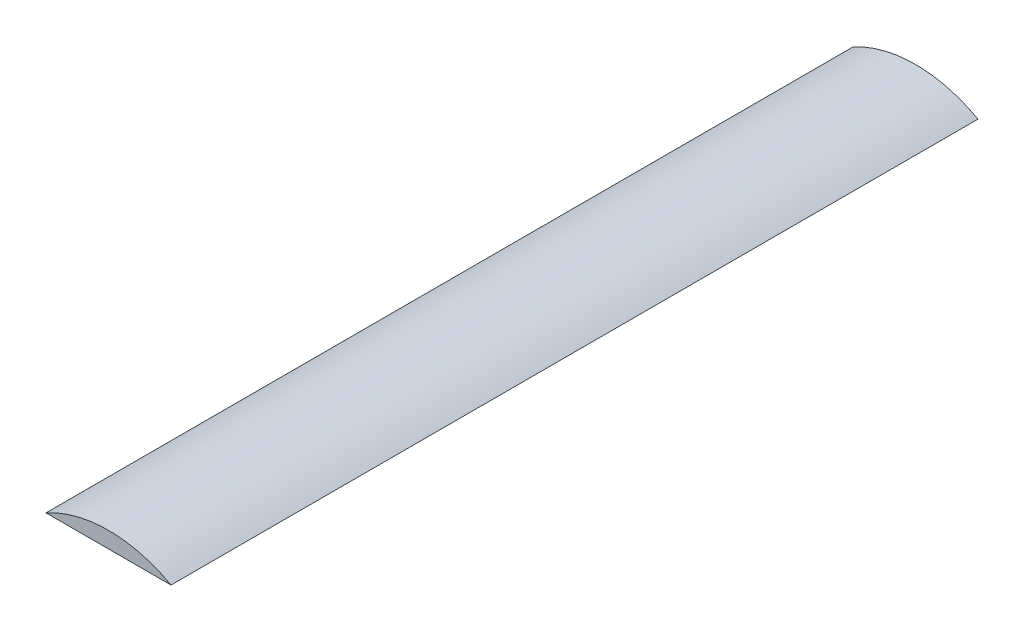
SolidWorks part; units mm, degrees
ref_plane "前视基准面" through (0, 0, 0) normal (0, 0, 1) x (1, 0, 0)
ref_plane "上视基准面" through (0, 0, 0) normal (0, 1, 0) x (1, 0, 0)
ref_plane "右视基准面" through (0, 0, 0) normal (1, 0, 0) x (0, 0, -1)
other "Configuration Table"
sketch "草图1" plane through (0, 0, 0) normal (0, 0, 1) x (1, 0, 0)
  line L1 (5, 3) -> (5, 1) construction
  line L2 (5, 1) -> (-2.746, 1)
  line L3 (5, 1) -> (12.746, 1)
  arc A0 (-2.746, 1) -> (12.746, 1) centre (5, -13) cw
  dimension "D1" = 16
  dimension "D2" = 2
extrude "凸台-拉伸1" add sketch "草图1" along normal blind 100
